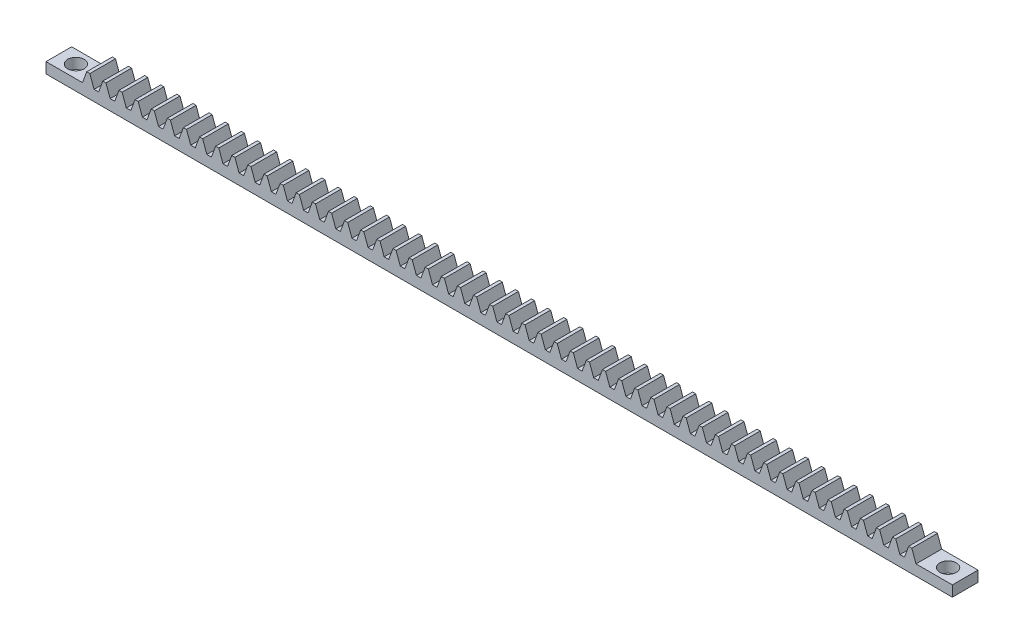
SolidWorks part; units mm, degrees
extrude "Blank" add sketch "BlankSke" against normal blind 4.5
sketch "BlankSke" plane through (0, 0, 0) normal (0, 0, 1) x (1, 0, 0)
  line L1 (0, 0) -> (147, 0)
  line L2 (0, 0) -> (0, 2.9)
  line L3 (0, 2.9) -> (147, 2.9)
  line L4 (147, 0) -> (147, 2.9)
  dimension "Length" = 147
  dimension "Blank_height" = 2.9
ref_plane "Plane1" through (0, 0, 0) normal (0, 0, 1) x (1, 0, 0)
ref_plane "Plane2" through (0, 0, 0) normal (0, 1, 0) x (1, 0, 0)
ref_plane "Plane3" through (0, 0, 0) normal (1, 0, 0) x (0, 0, -1)
other "Configuration Table"
sketch "HoldingSke" plane through (0, 0, 0) normal (0, 1, 0) x (1, 0, 0)
  line L0 (0, 0) -> (0.1546, 1.1003)
  line L1 (-15, 0) -> (100, 0) construction
  line L2 (0, 0) -> (-2.1039, 2.3779)
  line L3 (0, 0) -> (-11.863, 4.5341)
  line L4 (0, 0) -> (5.1973, 6.897)
  line L5 (0, 0) -> (-23.7986, -8.8762)
  line L6 (0, 0) -> (-10.5278, -7.1032)
  line L9 (-71.009, 38.7566) -> (67.1258, 89.0336)
  line L10 (-76.2, 3.2779) -> (-74.2, 3.2779)
  line L11 (0, 0) -> (-4.5, 0)
  line L12 (-76.2, 101.6) -> (-76.166, 101.6)
  line L13 (24.9733, 27.94) -> (52.9518, 28.4284)
  line L14 (24.9733, 27.94) -> (24.9743, 27.94)
  line L15 (24.9733, 27.94) -> (100.4006, 29.5858)
  circle A0 centre (0, 0) radius 19.05
  circle A1 centre (0, 0) radius 1
  circle A2 centre (0, 0) radius 12.7
  dimension "MPH" = 2
  dimension "Diameter" = 38.1
  dimension "Num_teeth" = 53
  dimension "Pitch" = 1.1111
  dimension "Show_teeth" = 998
  dimension "Thickness" = 12.7
  dimension "Ap" = 20
  dimension "Pitch_height" = 2
  dimension "Width" = 4.5
  dimension "Backlash" = 0.034
  dimension "Addendum_fac" = 1
  dimension "Dedendum_fac" = 1.25
  dimension "Clearance_fac" = 0.25
  dimension "Dedendum_add" = 0.001
  dimension "Length" = 147
  dimension "Module" = 0.9
sketch "TooCutSkeIll" plane through (0, 0, 0) normal (0, 0, 1) x (1, 0, 0)
  line L0 (-1.1278, 2.8763) -> (-0.4535, 1.0237)
  line L1 (-0.2411, 0.875) -> (0.2411, 0.875)
  line L2 (0.4535, 1.0237) -> (1.1278, 2.8763)
  line L3 (147, 2.9) -> (0, 2.9) construction
  line L4 (0, 0) -> (0, 64.897) construction
  line L5 (-13.208, 2) -> (12.954, 2) construction
  line L6 (0, 0) -> (147, 0) construction
  line L7 (0.8089, 2) -> (0.8089, 48.7463) construction
  line L8 (-0.8089, 2) -> (-0.8089, 48.7463) construction
  line L9 (1.1616, 2.9) -> (1.1616, 2.9254)
  line L10 (-1.1616, 2.9) -> (-1.1616, 2.9254)
  line L11 (-1.1616, 2.9254) -> (1.1616, 2.9254)
  arc A0 (0.2411, 0.875) -> (0.4535, 1.0237) centre (0.2411, 1.101) ccw
  arc A1 (-0.4535, 1.0237) -> (-0.2411, 0.875) centre (-0.2411, 1.101) ccw
  arc A2 (1.1616, 2.9) -> (1.1278, 2.8763) centre (1.1616, 2.864) ccw
  arc A3 (-1.1278, 2.8763) -> (-1.1616, 2.9) centre (-1.1616, 2.864) ccw
  dimension "Pitch_height" = 2
  dimension "Addendum_plus" = 0.9254
  dimension "Pressure_angle" = 20
  dimension "Gap_width" = 1.6177
  dimension "Dedendum" = 1.125
extrude "ToothCutIll" [suppressed] cut sketch "TooCutSkeIll" against normal through all
sketch "TooCutSkeSim" plane through (0, 0, 0) normal (0, 0, 1) x (1, 0, 0)
  line L0 (0.3994, 0.875) -> (-0.3994, 0.875)
  line L1 (1.1457, 2.9254) -> (0.3994, 0.875)
  line L2 (0, 17.4625) -> (0, 53.467) construction
  line L3 (1.1457, 2.9254) -> (-1.1457, 2.9254)
  line L6 (-1.1457, 2.9254) -> (-0.3994, 0.875)
  line L9 (-0.8089, 2) -> (0.8089, 2) construction
  line L10 (0, 0) -> (147, 0) construction
  line L11 (0.8089, 2) -> (0.8089, 53.467) construction
  line L12 (-0.8089, 2) -> (-0.8089, 53.467) construction
  dimension "Pitch_height" = 2
  dimension "Addendum_plus" = 0.9254
  dimension "Pressure_angle" = 20
  dimension "Gap_width" = 1.6177
  dimension "Dedendum" = 1.125
extrude "ToothCutSim" cut sketch "TooCutSkeSim" against normal through all
pattern_linear "TeethCuts" count 53 spacing 2.8274 along (1, 0, 0) of "ToothCutIll", "ToothCutSim"
sketch "Sketch1" plane through (147, 0, 0) normal (1, 0, 0) x (0, 0, -1)
  line L0 (0, 0) -> (0, 0.875) construction
  line L1 (0, 0.875) -> (4.5, 0.875)
  line L2 (0, 0.875) -> (0, 0)
  line L3 (0, 0) -> (4.5, 0)
  line L4 (4.5, 0.875) -> (4.5, 0)
  line L5 (0, 0.875) -> (4.5, 0.875) construction
  line L6 (4.5, 0) -> (4.5, 0.875) construction
extrude "Boss-Extrude1" add sketch "Sketch1" along normal blind 6
sketch "Sketch2" plane through (0, 0, 0) normal (-1, 0, 0) x (0, 0, 1)
  line L1 (-4.5, 0.875) -> (0, 0.875)
  line L2 (-4.5, 0.875) -> (-4.5, 0)
  line L3 (-4.5, 0) -> (0, 0)
  line L4 (0, 0.875) -> (0, 0)
extrude "Boss-Extrude2" add sketch "Sketch2" along normal blind 6
sketch "Sketch3" plane through (0, 0, 0) normal (0, -1, 0) x (1, 0, 0)
  line L0 (-6, -4.5) -> (-6, 0) construction
  line L1 (-6, 0) -> (153, 0)
  line L2 (-6, 0) -> (-6, -4.5)
  line L3 (-6, -4.5) -> (153, -4.5)
  line L4 (153, 0) -> (153, -4.5)
extrude "Boss-Extrude3" add sketch "Sketch3" along normal blind 1
sketch "Sketch4" plane through (0, 0.875, 0) normal (0, 1, 0) x (1, 0, 0)
  line L0 (-6, 2.25) -> (153, 2.25) construction
  line L1 (-6, 0) -> (-6, 4.5) construction
  line L2 (153, 4.5) -> (153, 0) construction
  line L3 (73.5, 2.25) -> (73.5133, 4.5) construction
  line L4 (73.1139, 4.5) -> (73.9127, 4.5) construction
  circle A0 centre (150, 2.25) radius 1.45
  circle A1 centre (-3, 2.25) radius 1.45
  point P14 (0, 0)
  dimension "D1" = 3
  dimension "D2" = 3
extrude "Cut-Extrude1" cut sketch "Sketch4" against normal up to next
equation "' \"Module@HoldingSke\" = 6.35"
equation "' \"Num_teeth@HoldingSke\" = 12"
equation "' \"Ap@HoldingSke\" =  20"
equation "' \"Ap@HoldingSke\" = 20"
equation "' \"Width@HoldingSke\" = 0.25 * 25.4"
equation "' \"Show_teeth@HoldingSke\" = 500"
equation "' \"Backlash@HoldingSke\" = 0.009 * 25.4"
equation "' \"Addendum_fac@HoldingSke\" = 1.0"
equation "' \"Dedendum_fac@HoldingSke\" = 1.25"
equation "' \"Dedendum_add@HoldingSke\" = 0.00005 * 25.4"
equation "' \"Clearance_fac@HoldingSke\" = 0.25"
equation "' \"Pitch_height@HoldingSke\" = 1 * 25.4"
equation "' \"Length@HoldingSke\" = 4.71 * 25.4"
equation "\"Pitch@HoldingSke\" = 1 / \"Module@HoldingSke\""
equation "\"MPH@HoldingSke\" = \"Dedendum_fac@HoldingSke\" / \"Pitch@HoldingSke\" + 2 * \"Dedendum_add@HoldingSke\" + 0.002 * 25.4"
equation "\"MPH@HoldingSke\" = ((sgn( \"MPH@HoldingSke\" - \"Pitch_height@HoldingSke\")+1)*( \"MPH@HoldingSke\" - \"Pitch_height@HoldingSke\"))/2 + \"Pitch_height@HoldingSke\""
equation "\"Blank_height@BlankSke\" = \"Pitch_height@HoldingSke\" + \"Addendum_fac@HoldingSke\"  / \"Pitch@HoldingSke\" "
equation "\"Length@BlankSke\" =  \"Length@HoldingSke\""
equation "\"Face_width@Blank\" = \"Width@HoldingSke\""
equation "\"Pressure_angle@TooCutSkeIll\" = \"Ap@HoldingSke\""
equation "\"Addendum_plus@TooCutSkeIll\" =  \"Addendum_fac@HoldingSke\"  / \"Pitch@HoldingSke\" + 0.001 *25.4"
equation "\"Dedendum@TooCutSkeIll\" = \"Dedendum_fac@HoldingSke\"  / \"Pitch@HoldingSke\""
equation "\"Pitch_height@TooCutSkeIll\" =  \"MPH@HoldingSke\""
equation "\"Gap_width@TooCutSkeIll\" = 3.14159265 / 2 / \"Pitch@HoldingSke\" + 6 * \"Backlash@HoldingSke\""
equation "\"Pressure_angle@TooCutSkeSim\" = \"Ap@HoldingSke\""
equation "\"Addendum_plus@TooCutSkeSim\" =  \"Addendum_fac@HoldingSke\"  / \"Pitch@HoldingSke\" + 0.001 * 25.4"
equation "\"Dedendum@TooCutSkeSim\" = \"Dedendum_fac@HoldingSke\"  / \"Pitch@HoldingSke\""
equation "\"Pitch_height@TooCutSkeSim\" =  \"MPH@HoldingSke\""
equation "\"Gap_width@TooCutSkeSim\" = 3.14159265 / 2 / \"Pitch@HoldingSke\" + 6 * \"Backlash@HoldingSke\""
equation "\"Root_fillet@TooCutSkeIll\" = \"Clearance_fac@HoldingSke\" / \"Pitch@HoldingSke\" + \"Dedendum_add@HoldingSke\""
equation "\"Break_rad@TooCutSkeIll\" = 0.02 / \"Pitch@HoldingSke\" * 2"
equation "\"Linear_pitch@TeethCuts\" = 3.14159265 / \"Pitch@HoldingSke\""
equation "\"Num_teeth@HoldingSke\" = int( ( \"Length@HoldingSke\" + 0 ) / (3.14159265 / \"Pitch@HoldingSke\")) + 0.9999  + 1"
equation " \"Num_teeth@TeethCuts\" = int( \"Show_teeth@HoldingSke\" ) + 1"
equation " \"Num_teeth@TeethCuts\" = ((sgn( \"Num_teeth@TeethCuts\" - \"Num_teeth@HoldingSke\" )-1)*( \"Num_teeth@TeethCuts\" - \"Num_teeth@HoldingSke\" ))/-2+ \"Num_teeth@HoldingSke\""
equation " \"Num_teeth@TeethCuts\" = ((sgn( \"Num_teeth@TeethCuts\" - 2.0)+1)*( \"Num_teeth@TeethCuts\" - 2.0))/2 +2.0"
